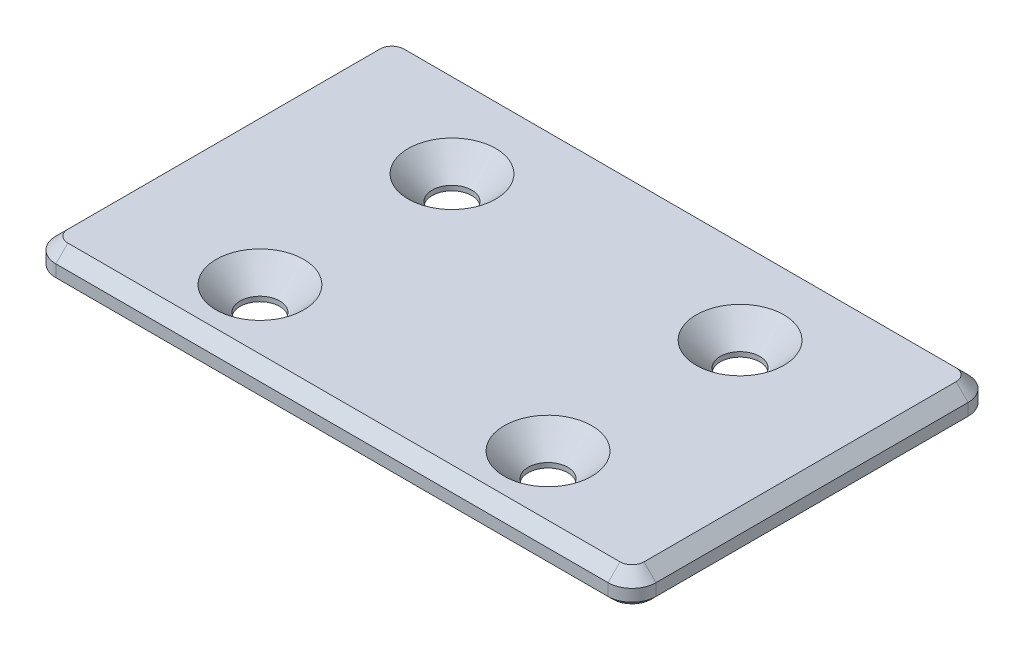
SolidWorks part; units mm, degrees
ref_plane "前视基准面" through (0, 0, 0) normal (0, 0, 1) x (1, 0, 0)
ref_plane "上视基准面" through (0, 0, 0) normal (0, 1, 0) x (1, 0, 0)
ref_plane "右视基准面" through (0, 0, 0) normal (1, 0, 0) x (0, 0, -1)
other "Configuration Table"
sketch "草图1" plane through (0, 0, 0) normal (0, 1, 0) x (1, 0, 0)
  line L1 (0, 0) -> (50, 0)
  line L2 (0, 0) -> (0, 30)
  line L3 (0, 30) -> (50, 30)
  line L4 (50, 0) -> (50, 30)
  dimension "D1" = 30
  dimension "D2" = 50
extrude "凸台-拉伸1" add sketch "草图1" along normal blind 2.4
sketch "草图2" plane through (0, 2.4, 0) normal (0, 1, 0) x (1, 0, 0)
  line L0 (0, 0) -> (50, 0) construction
  circle A0 centre (13, 6) radius 1.65
  circle A1 centre (37, 6) radius 1.65
  circle A2 centre (13, 22) radius 1.65
  circle A3 centre (37, 22) radius 1.65
  point P6 (25, 0)
  dimension "D1" = 3.3
  dimension "D2" = 3.3
  dimension "D3" = 6
  dimension "D4" = 6
  dimension "D5" = 12
  dimension "D6" = 12
  dimension "D7" = 2
extrude "切除-拉伸1" cut sketch "草图2" against normal through all contours A2 | A0 | A3 | A1
chamfer "倒角1" distance 2 angle 45 4 edges at (37, 2.4, -4.35) (13, 2.4, -4.35) (37, 2.4, -20.35) (13, 2.4, -20.35)
fillet "圆角1" radius 2 4 edges at (50, 1.2, -30) (50, 1.2, 0) (0, 1.2, 0) (0, 1.2, -30)
chamfer "倒角2" distance 1 angle 45 8 edges at (25, 2.4, 0) (49.4142, 2.4, -0.5858) (0.5858, 2.4, -0.5858) (50, 2.4, -15) (0, 2.4, -15) (49.4142, 2.4, -29.4142) (0.5858, 2.4, -29.4142) (25, 2.4, -30)
chamfer "倒角3" distance 0.4 angle 45 8 edges at (25, 0, 0) (49.4142, 0, -0.5858) (0.5858, 0, -0.5858) (50, 0, -15) (0, 0, -15) (49.4142, 0, -29.4142) (0.5858, 0, -29.4142) (25, 0, -30)
